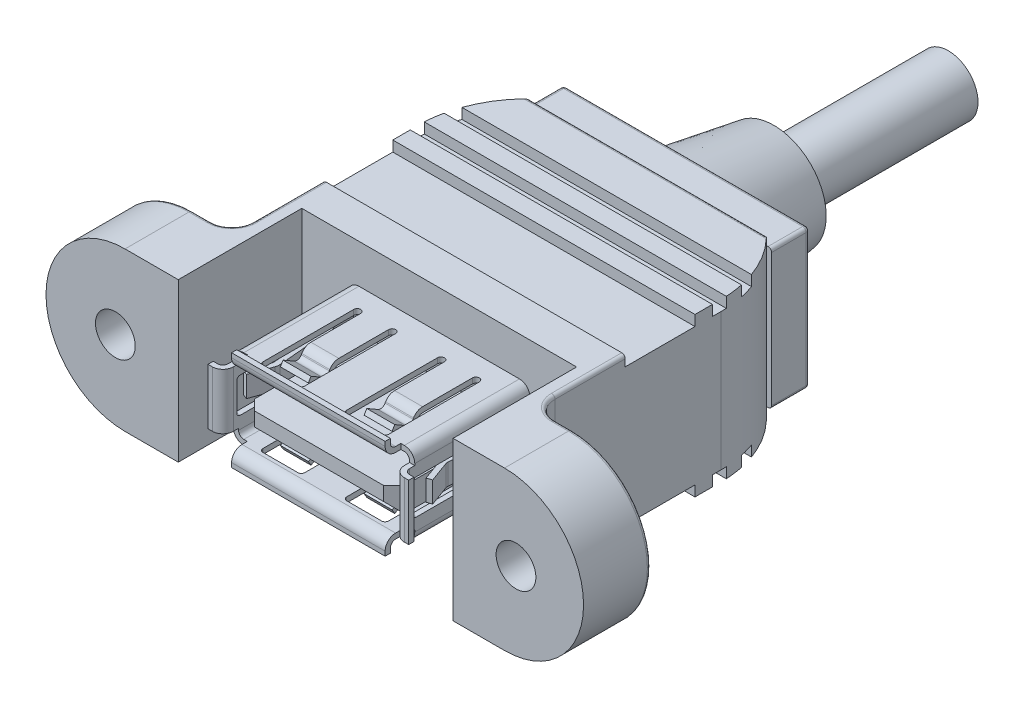
SolidWorks part; units mm, degrees
ref_plane "Front Plane" through (0, 0, 0) normal (0, 0, 1) x (1, 0, 0)
ref_plane "Top Plane" through (0, 0, 0) normal (0, 1, 0) x (1, 0, 0)
ref_plane "Right Plane" through (0, 0, 0) normal (1, 0, 0) x (0, 0, -1)
sketch "Sketch1" plane through (0, 0, 0) normal (0, 1, 0) x (1, 0, 0)
  line L0 (0, 0) -> (0, 57.7309) construction
  line L1 (-10.0012, 0) -> (-10.0013, -8.9916)
  line L2 (-10.0012, 0) -> (10.0012, 0)
  line L3 (-10.9982, -8.9916) -> (-10.9982, 9.525)
  line L4 (-8.5691, 15.24) -> (8.5691, 15.24)
  line L5 (10.9982, -8.9916) -> (10.9982, 9.525)
  line L6 (10.0012, 0) -> (10.0013, -8.9916)
  line L7 (-10.9982, -8.9916) -> (-10.0013, -8.9916)
  line L8 (10.0013, -8.9916) -> (10.9982, -8.9916)
  arc A0 (-8.5691, 15.24) -> (-10.9982, 9.525) centre (-3.0607, 9.525) ccw
  arc A1 (10.9982, 9.525) -> (8.5691, 15.24) centre (3.0607, 9.525) ccw
  dimension "D6" = 15.875
  dimension "D1" = 21.9964
  dimension "D2" = 15.24
  dimension "D3" = 20.0025
  dimension "D4" = 8.9916
  dimension "D5" = 9.525
  dimension "D7" = 10.9982
extrude "Extrude1" add sketch "Sketch1" along normal mid plane 11.5062
sketch "Sketch2" plane through (0, 0, -15.24) normal (0, 0, -1) x (-1, 0, 0)
  line L0 (0, 0) -> (-8.9535, 0) construction
  line L1 (-8.9535, 5.08) -> (8.9535, 5.08)
  line L2 (-8.9535, 5.08) -> (-8.9535, -5.08)
  line L3 (-8.9535, -5.08) -> (8.9535, -5.08)
  line L4 (8.9535, 5.08) -> (8.9535, -5.08)
  line L5 (0, 0) -> (0, -5.08) construction
  dimension "D1" = 17.907
  dimension "D2" = 10.16
extrude "Extrude2" add sketch "Sketch2" along normal blind 2.7686
sketch "Sketch3" plane through (0, 0, 8.9916) normal (0, 0, 1) x (1, 0, 0)
  line L0 (-10.9982, -5.7531) -> (-10.0013, -5.7531) construction
  line L1 (10.0012, 5.7531) -> (13.7458, 5.7531)
  line L2 (10.0012, 5.7531) -> (10.0013, -5.7531)
  line L3 (10.0013, -5.7531) -> (13.7458, -5.7531)
  line L5 (-10.0013, 5.7531) -> (-13.8758, 5.7531)
  line L6 (-10.0013, 5.7531) -> (-10.0012, -5.7531)
  line L7 (-10.0012, -5.7531) -> (-13.8758, -5.7531)
  line L9 (10.0013, -5.7531) -> (10.9982, -5.7531) construction
  arc A0 (-13.8758, 5.7531) -> (-13.8758, -5.7531) centre (-13.8758, 0) ccw
  arc A1 (13.7458, 5.7531) -> (13.7458, -5.7531) centre (13.7458, 0) cw
  dimension "D1" = 9.4976
  dimension "D2" = 9.6276
extrude "Extrude3" add sketch "Sketch3" against normal blind 4.9
sketch "Sketch4" plane through (0, 0, 0) normal (0, 1, 0) x (1, 0, 0)
  line L0 (-10.9982, -1.5516) -> (-12.7762, -4.0916)
  line L1 (10.9982, -1.5516) -> (12.7762, -4.0916)
  line L2 (-10.9982, 9.525) -> (-10.9982, -4.0916) construction
  line L3 (-10.9982, -1.5516) -> (-10.9982, -4.0916)
  line L4 (-10.9982, -4.0916) -> (-13.8758, -4.0916) construction
  line L5 (-10.9982, -4.0916) -> (-12.7762, -4.0916)
  line L6 (10.9982, -4.0916) -> (10.9982, 9.525) construction
  line L7 (10.9982, -4.0916) -> (10.9982, -1.5516)
  line L8 (13.7458, -4.0916) -> (10.9982, -4.0916) construction
  line L9 (12.7762, -4.0916) -> (10.9982, -4.0916)
  dimension "D1" = 2.54
  dimension "D2" = 1.778
extrude "Extrude4" add sketch "Sketch4" along normal mid plane 2.54
sketch "Sketch5" plane through (0, 0, 8.9916) normal (0, 0, 1) x (1, 0, 0)
  line L0 (0, 0) -> (0, 11.1761) construction
  line L1 (-7.2517, 3.4036) -> (7.2517, 3.4036) construction
  line L2 (-7.2517, 3.4036) -> (-7.2517, -3.4036) construction
  line L3 (-7.2517, -3.4036) -> (7.2517, -3.4036) construction
  line L4 (7.2517, 3.4036) -> (7.2517, -3.4036) construction
  line L5 (-14.5801, 0) -> (14.5801, 0) construction
  circle A0 centre (-14.5801, 0) radius 1.4478
  circle A1 centre (14.5801, 0) radius 1.4478
  point P8 (0, 3.4036)
  point P9 (0, 0)
  dimension "D3" = 2.8956
  dimension "D1" = 7.3284
  dimension "D5" = 14.5034
  dimension "D7" = 6.8072
  dimension "D8" = 3.4036
extrude "Cut-Extrude1" cut sketch "Sketch5" against normal up to surface (4.9 mm away) up to face at (-12.8812, 0, 4.0916)
sketch "Sketch6" plane through (0, 0, 0) normal (0, 1, 0) x (1, 0, 0)
  line L0 (0, 27.38) -> (0, 9.0652) construction
  line L1 (-8.9535, 18.0086) -> (8.9535, 18.0086) construction
  line L2 (0, 18.0086) -> (4.826, 18.0086)
  line L3 (0, 24.3586) -> (3.81, 24.3586)
  line L4 (3.81, 24.3586) -> (4.826, 18.0086)
  line L5 (0, 24.3586) -> (0, 18.0086)
  dimension "D1" = 9.652
  dimension "D2" = 7.62
  dimension "D3" = 6.35
revolve "Revolve1" add sketch "Sketch6" angle 360 about L0
sketch "Sketch9" plane through (0, 0, -24.3586) normal (0, 0, -1) x (-1, 0, 0)
  circle A0 centre (0, 0) radius 2.159
  dimension "D1" = 4.318
extrude "Extrude5" add sketch "Sketch9" along normal blind 12.7
sketch "Sketch7" plane through (0, -5.7531, 0) normal (0, -1, 0) x (1, 0, 0)
  line L0 (0, -2.54) -> (0, 0) construction
  line L1 (17.272, -2.54) -> (-17.272, -2.54)
  line L2 (17.78, -3.048) -> (17.78, -7.112)
  line L3 (17.272, -7.62) -> (-17.272, -7.62)
  line L4 (-17.78, -3.048) -> (-17.78, -7.112)
  line L5 (17.272, -8.89) -> (-17.272, -8.89)
  line L6 (-10.0012, 0) -> (10.0012, 0) construction
  line L7 (17.272, -9.906) -> (-17.272, -9.906)
  line L8 (0, -2.54) -> (0, -8.89) construction
  line L9 (16.256, -11.176) -> (-16.256, -11.176)
  line L11 (16.256, -12.192) -> (-16.256, -12.192)
  arc A0 (17.272, -8.89) -> (17.272, -9.906) centre (17.272, -9.398) cw
  arc A1 (16.256, -11.176) -> (16.256, -12.192) centre (16.256, -11.684) cw
  arc A2 (-16.256, -12.192) -> (-16.256, -11.176) centre (-16.256, -11.684) cw
  arc A3 (-17.272, -9.906) -> (-17.272, -8.89) centre (-17.272, -9.398) cw
  arc A4 (17.272, -7.62) -> (17.78, -7.112) centre (17.272, -7.112) ccw
  arc A5 (-17.78, -7.112) -> (-17.272, -7.62) centre (-17.272, -7.112) ccw
  arc A6 (-17.272, -2.54) -> (-17.78, -3.048) centre (-17.272, -3.048) ccw
  arc A7 (17.272, -2.54) -> (17.78, -3.048) centre (17.272, -3.048) cw
  dimension "D1" = 0.508
  dimension "D7" = 35.56
  dimension "D9" = 33.528
  dimension "D10" = 16.764
  dimension "D2" = 35.56
  dimension "D3" = 2.54
  dimension "D4" = 5.08
  dimension "D5" = 1.27
  dimension "D6" = 1.27
  dimension "D8" = 1.016
extrude "Cut-Extrude2" cut sketch "Sketch7" against normal blind 0.762
sketch "Sketch8" plane through (0, 5.7531, 0) normal (0, 1, 0) x (-1, 0, 0)
  line L2 (16.256, -11.176) -> (-16.256, -11.176)
  line L3 (-16.256, -12.192) -> (16.256, -12.192)
  line L4 (16.256, -11.176) -> (-16.256, -11.176)
  line L5 (-16.256, -12.192) -> (16.256, -12.192)
  line L6 (17.272, -8.89) -> (-17.272, -8.89)
  line L7 (-17.272, -9.906) -> (17.272, -9.906)
  line L8 (17.272, -8.89) -> (-17.272, -8.89)
  line L9 (-17.272, -9.906) -> (17.272, -9.906)
  line L12 (17.272, -2.54) -> (-17.272, -2.54)
  line L13 (17.78, -7.112) -> (17.78, -3.048)
  line L14 (-17.272, -7.62) -> (17.272, -7.62)
  line L15 (-17.78, -3.048) -> (-17.78, -7.112)
  line L16 (17.272, -2.54) -> (-17.272, -2.54)
  line L17 (17.78, -7.112) -> (17.78, -3.048)
  line L18 (-17.272, -7.62) -> (17.272, -7.62)
  line L19 (-17.78, -3.048) -> (-17.78, -7.112)
  arc A2 (16.256, -12.192) -> (16.256, -11.176) centre (16.256, -11.684) ccw
  arc A3 (-16.256, -11.176) -> (-16.256, -12.192) centre (-16.256, -11.684) ccw
  arc A4 (16.256, -12.192) -> (16.256, -11.176) centre (16.256, -11.684) ccw
  arc A5 (-16.256, -11.176) -> (-16.256, -12.192) centre (-16.256, -11.684) ccw
  arc A6 (17.272, -9.906) -> (17.272, -8.89) centre (17.272, -9.398) ccw
  arc A7 (-17.272, -8.89) -> (-17.272, -9.906) centre (-17.272, -9.398) ccw
  arc A8 (17.272, -9.906) -> (17.272, -8.89) centre (17.272, -9.398) ccw
  arc A9 (-17.272, -8.89) -> (-17.272, -9.906) centre (-17.272, -9.398) ccw
  arc A12 (17.78, -3.048) -> (17.272, -2.54) centre (17.272, -3.048) ccw
  arc A13 (17.272, -7.62) -> (17.78, -7.112) centre (17.272, -7.112) ccw
  arc A14 (-17.78, -7.112) -> (-17.272, -7.62) centre (-17.272, -7.112) ccw
  arc A15 (-17.272, -2.54) -> (-17.78, -3.048) centre (-17.272, -3.048) ccw
  arc A16 (17.78, -3.048) -> (17.272, -2.54) centre (17.272, -3.048) ccw
  arc A17 (17.272, -7.62) -> (17.78, -7.112) centre (17.272, -7.112) ccw
  arc A18 (-17.78, -7.112) -> (-17.272, -7.62) centre (-17.272, -7.112) ccw
  arc A19 (-17.272, -2.54) -> (-17.78, -3.048) centre (-17.272, -3.048) ccw
  dimension "D1" = 0
  dimension "D2" = 0
  dimension "D3" = 0
extrude "Cut-Extrude3" cut sketch "Sketch8" against normal blind 0.762
fillet "Fillet1" radius 1.524 4 edges at (-10.9982, -3.5116, 4.0916) (-10.9982, 3.5116, 4.0916) (10.9982, -3.5116, 4.0916) (10.9982, 3.5116, 4.0916)
fillet "Fillet2" radius 0.254 24 edges at (0, -5.7531, -15.24) (-10.9982, -5.7531, 0.0138) (-10.9982, 5.7531, 0.0138) (-13.199, 5.7531, 4.0916) (10.9982, 5.7531, 0.0138) (10.9982, -5.7531, 0.0138) (13.134, -5.7531, 4.0916) (-11.4446, -5.7531, 3.6452) (-11.4446, 5.7531, 3.6452) (11.4446, -5.7531, 3.6452) (11.4446, 5.7531, 3.6452) (8.9535, 5.08, -16.6243) (8.9535, -5.08, -16.6243) (-8.9535, -5.08, -16.6243) (-8.9535, 5.08, -16.6243) (8.9535, 0, -18.0086) (0, -5.08, -18.0086) (-8.9535, 0, -18.0086) (0, 5.08, -18.0086) (13.134, 5.7531, 4.0916) (19.4989, 0, 4.0916) (-13.199, -5.7531, 4.0916) (-19.6289, 0, 4.0916) (0, 5.7531, -15.24)
sketch "Sketch10" plane through (0, 0, 0) normal (0, 0, 1) x (1, 0, 0)
  line L0 (-22.3107, 0) -> (0, 0) construction
  line L1 (0, 8.8149) -> (0, -8.8149) construction
  line L2 (-5.842, 2.54) -> (5.842, 2.54)
  line L3 (-5.842, 2.921) -> (5.842, 2.921)
  line L4 (-6.604, 2.159) -> (-6.604, -2.159)
  line L5 (-5.842, -2.921) -> (5.842, -2.921)
  line L6 (6.604, 2.159) -> (6.604, -2.159)
  line L7 (6.223, 2.159) -> (6.223, -2.159)
  line L8 (-5.842, -2.54) -> (5.842, -2.54)
  line L9 (-6.223, 2.159) -> (-6.223, -2.159)
  arc A0 (-6.604, 2.159) -> (-5.842, 2.921) centre (-5.842, 2.159) cw
  arc A1 (-5.842, -2.921) -> (-6.604, -2.159) centre (-5.842, -2.159) cw
  arc A2 (6.604, -2.159) -> (5.842, -2.921) centre (5.842, -2.159) cw
  arc A3 (5.842, 2.921) -> (6.604, 2.159) centre (5.842, 2.159) cw
  arc A4 (-6.223, 2.159) -> (-5.842, 2.54) centre (-5.842, 2.159) cw
  arc A5 (5.842, 2.54) -> (6.223, 2.159) centre (5.842, 2.159) cw
  arc A6 (6.223, -2.159) -> (5.842, -2.54) centre (5.842, -2.159) cw
  arc A7 (-5.842, -2.54) -> (-6.223, -2.159) centre (-5.842, -2.159) cw
  point P13 (-6.604, -2.921)
  point P16 (6.604, -2.921)
  dimension "D6" = 0.762
  dimension "D2" = 13.208
  dimension "D3" = 6.604
  dimension "D4" = 5.842
  dimension "D5" = 2.921
  dimension "D7" = 0.381
extrude "Extrude6" add sketch "Sketch10" along normal blind 8.382
sketch "Sketch11" plane through (0, 0, 8.382) normal (0, 0, 1) x (1, 0, 0)
  line L0 (-6.604, 2.159) -> (-6.604, -2.159) construction
  line L1 (-6.604, 2.032) -> (-6.223, 2.032)
  line L2 (-6.604, 2.032) -> (-6.604, -2.032)
  line L3 (-6.604, -2.032) -> (-6.223, -2.032)
  line L4 (-6.223, 2.032) -> (-6.223, -2.032)
  line L5 (-6.223, 2.159) -> (-6.223, -2.159) construction
  line L6 (-5.842, -2.54) -> (5.842, -2.54) construction
  line L7 (-5.588, -2.54) -> (5.588, -2.54)
  line L8 (-5.588, -2.54) -> (-5.588, -2.921)
  line L9 (-5.588, -2.921) -> (5.588, -2.921)
  line L10 (5.588, -2.54) -> (5.588, -2.921)
  line L11 (-5.842, -2.921) -> (5.842, -2.921) construction
  line L12 (5.842, 2.921) -> (-5.842, 2.921) construction
  line L13 (-5.588, 2.921) -> (5.588, 2.921)
  line L14 (-5.588, 2.921) -> (-5.588, 2.54)
  line L15 (-5.588, 2.54) -> (5.588, 2.54)
  line L16 (5.588, 2.921) -> (5.588, 2.54)
  line L17 (5.842, 2.54) -> (-5.842, 2.54) construction
  line L18 (6.223, -2.159) -> (6.223, 2.159) construction
  line L19 (6.223, 2.032) -> (6.604, 2.032)
  line L20 (6.223, 2.032) -> (6.223, -2.032)
  line L21 (6.223, -2.032) -> (6.604, -2.032)
  line L22 (6.604, 2.032) -> (6.604, -2.032)
  line L23 (6.604, -2.159) -> (6.604, 2.159) construction
  dimension "D1" = 11.176
  dimension "D2" = 4.064
  dimension "D3" = 0.889
  dimension "D4" = 1.016
extrude "Extrude7" add sketch "Sketch11" along normal blind 0.254
sketch "Sketch12" plane through (5.588, 0, 0) normal (1, 0, 0) x (0, 0, -1)
  line L0 (-9.525, 3.302) -> (-9.525, 3.6195)
  line L1 (-9.144, 3.302) -> (-9.144, 3.6195)
  line L2 (-9.525, 3.6195) -> (-9.144, 3.6195)
  line L3 (-9.525, -3.302) -> (-9.525, -3.6195)
  line L4 (-8.382, 2.54) -> (-8.382, 2.921)
  line L5 (-8.382, 2.921) -> (-8.636, 2.921)
  line L6 (-8.636, 2.921) -> (-8.636, 2.54)
  line L7 (-8.636, 2.54) -> (-8.382, 2.54)
  line L8 (-8.382, 2.54) -> (-8.382, 2.921)
  line L9 (-8.382, 2.921) -> (-8.763, 2.921)
  line L10 (-8.382, -2.921) -> (-8.382, -2.54)
  line L11 (-8.763, 2.54) -> (-8.382, 2.54)
  line L12 (-8.382, -2.54) -> (-8.636, -2.54)
  line L13 (-8.636, -2.54) -> (-8.636, -2.921)
  line L14 (-8.636, -2.921) -> (-8.382, -2.921)
  line L15 (-8.382, -2.921) -> (-8.382, -2.54)
  line L16 (-8.382, -2.54) -> (-8.763, -2.54)
  line L17 (-9.144, -3.302) -> (-9.144, -3.6195)
  line L18 (-8.763, -2.921) -> (-8.382, -2.921)
  line L19 (-9.525, -3.6195) -> (-9.144, -3.6195)
  line L20 (0, 0) -> (-11.5715, 0) construction
  line L25 (0, 5.7531) -> (0, -5.7531) construction
  arc A0 (-8.763, 2.54) -> (-9.525, 3.302) centre (-8.763, 3.302) cw
  arc A1 (-8.763, -2.54) -> (-9.525, -3.302) centre (-8.763, -3.302) ccw
  arc A2 (-8.763, 2.921) -> (-9.144, 3.302) centre (-8.763, 3.302) cw
  arc A3 (-8.763, -2.921) -> (-9.144, -3.302) centre (-8.763, -3.302) ccw
  dimension "D7" = 0.762
  dimension "D8" = 0.381
  dimension "D3" = 1.0795
  dimension "D4" = 1.0795
  dimension "D5" = 0.381
  dimension "D6" = 9.525
  dimension "D1" = 0
  dimension "D2" = 0
extrude "Extrude8" add sketch "Sketch12" against normal blind 11.176
sketch "Sketch13" plane through (0, 2.032, 0) normal (0, 1, 0) x (-1, 0, 0)
  line L0 (-6.985, 9.144) -> (-7.3025, 9.144)
  line L1 (-7.3025, 9.144) -> (-7.3025, 9.525)
  line L2 (-7.3025, 9.525) -> (-6.985, 9.525)
  line L3 (6.985, 9.144) -> (7.3025, 9.144)
  line L4 (6.223, 8.382) -> (6.604, 8.382)
  line L5 (6.604, 8.382) -> (6.604, 8.636)
  line L6 (6.604, 8.636) -> (6.223, 8.636)
  line L7 (6.223, 8.636) -> (6.223, 8.382)
  line L8 (6.223, 8.382) -> (6.604, 8.382)
  line L9 (6.604, 8.382) -> (6.604, 8.763)
  line L10 (7.3025, 9.144) -> (7.3025, 9.525)
  line L11 (6.223, 8.763) -> (6.223, 8.382)
  line L12 (-6.604, 8.382) -> (-6.223, 8.382)
  line L13 (-6.223, 8.382) -> (-6.223, 8.636)
  line L14 (-6.223, 8.636) -> (-6.604, 8.636)
  line L15 (-6.604, 8.636) -> (-6.604, 8.382)
  line L16 (-6.604, 8.382) -> (-6.223, 8.382)
  line L17 (-6.223, 8.382) -> (-6.223, 8.763)
  line L18 (7.3025, 9.525) -> (6.985, 9.525)
  line L19 (-6.604, 8.763) -> (-6.604, 8.382)
  line L20 (5.588, 9.525) -> (-5.588, 9.525) construction
  arc A0 (-6.985, 9.144) -> (-6.604, 8.763) centre (-6.985, 8.763) cw
  arc A1 (6.985, 9.144) -> (6.604, 8.763) centre (6.985, 8.763) ccw
  arc A2 (-6.223, 8.763) -> (-6.985, 9.525) centre (-6.985, 8.763) ccw
  arc A3 (6.985, 9.525) -> (6.223, 8.763) centre (6.985, 8.763) ccw
  point P26 (6.223, 9.525)
  dimension "D6" = 0.381
  dimension "D7" = 0.762
  dimension "D3" = 0.381
  dimension "D4" = 1.0795
  dimension "D5" = 1.0795
  dimension "D1" = 0
  dimension "D2" = 0
extrude "Extrude9" add sketch "Sketch13" against normal up to surface (4.064 mm away) up to face at (-6.4611, -2.032, 8.5725)
sketch "Sketch14" plane through (0, 2.921, 0) normal (0, 1, 0) x (-1, 0, 0)
  line L0 (0, 0) -> (0, 2.9776) construction
  line L1 (-2.032, 1.651) -> (-2.032, 2.159)
  line L2 (4.572, 1.651) -> (4.572, 8.255)
  line L3 (4.318, 8.509) -> (1.778, 8.509)
  line L4 (1.524, 1.651) -> (1.524, 8.255)
  line L5 (-3.048, 8.509) -> (-3.048, 0.7388) construction
  line L6 (-1.524, 1.651) -> (-1.524, 8.255)
  line L7 (-1.778, 8.509) -> (-4.318, 8.509)
  line L8 (-4.572, 1.651) -> (-4.572, 8.255)
  line L9 (-5.842, 0) -> (5.842, 0) construction
  line L10 (3.048, 8.509) -> (3.048, 0.7388) construction
  line L11 (-2.032, 2.159) -> (-4.064, 2.159)
  line L12 (5.588, 9.525) -> (-5.588, 9.525) construction
  line L13 (-4.064, 2.159) -> (-4.064, 1.651)
  line L14 (4.064, 1.651) -> (4.064, 2.159)
  line L15 (4.064, 2.159) -> (2.032, 2.159)
  line L16 (2.032, 2.159) -> (2.032, 1.651)
  arc A0 (-4.572, 8.255) -> (-4.318, 8.509) centre (-4.318, 8.255) cw
  arc A1 (-1.524, 8.255) -> (-1.778, 8.509) centre (-1.778, 8.255) ccw
  arc A2 (-2.032, 1.651) -> (-1.524, 1.651) centre (-1.778, 1.651) ccw
  arc A3 (-4.572, 1.651) -> (-4.064, 1.651) centre (-4.318, 1.651) ccw
  arc A4 (2.032, 1.651) -> (1.524, 1.651) centre (1.778, 1.651) cw
  arc A5 (4.572, 1.651) -> (4.064, 1.651) centre (4.318, 1.651) cw
  arc A6 (4.318, 8.509) -> (4.572, 8.255) centre (4.318, 8.255) cw
  arc A7 (1.524, 8.255) -> (1.778, 8.509) centre (1.778, 8.255) cw
  dimension "D6" = 7.112
  dimension "D1" = 0.254
  dimension "D7" = 0.762
  dimension "D2" = 1.016
  dimension "D3" = 3.048
  dimension "D4" = 6.096
  dimension "D5" = 3.048
extrude "Cut-Extrude4" cut sketch "Sketch14" against normal up to surface (5.842 mm away) up to face at (0, -2.921, 6.3818)
sketch "Sketch15" plane through (6.604, 0, 0) normal (1, 0, 0) x (0, 0, -1)
  line L0 (0, 0) -> (-4.7284, 0) construction
  line L1 (0, -2.159) -> (0, 2.159) construction
  line L2 (-9.525, -2.032) -> (-9.525, 2.032) construction
  line L3 (-8.255, 1.27) -> (-1.651, 1.27)
  line L4 (-8.509, 1.016) -> (-8.509, -1.016)
  line L5 (-8.255, -1.27) -> (-1.651, -1.27)
  line L6 (-1.651, 0.762) -> (-1.905, 0.762)
  line L7 (-1.905, 0.762) -> (-1.905, -0.762)
  line L8 (-1.905, -0.762) -> (-1.651, -0.762)
  arc A0 (-8.509, 1.016) -> (-8.255, 1.27) centre (-8.255, 1.016) cw
  arc A1 (-8.255, -1.27) -> (-8.509, -1.016) centre (-8.255, -1.016) cw
  arc A2 (-1.651, -0.762) -> (-1.651, -1.27) centre (-1.651, -1.016) cw
  arc A3 (-1.651, 1.27) -> (-1.651, 0.762) centre (-1.651, 1.016) cw
  point P12 (-8.509, 1.27)
  point P15 (-8.509, -1.27)
  dimension "D5" = 0.254
  dimension "D2" = 7.112
  dimension "D6" = 0.508
  dimension "D1" = 1.016
  dimension "D3" = 1.27
  dimension "D4" = 2.54
extrude "Cut-Extrude5" cut sketch "Sketch15" against normal blind 13.462
sketch "Sketch17" plane through (4.064, 0, 0) normal (1, 0, 0) x (0, 0, -1)
  line L0 (-5.935, 2.54) -> (-5.9716, 2.4765)
  line L1 (-8.509, 2.54) -> (-8.509, 2.921) construction
  line L2 (-6.4921, 2.337) -> (-7.3025, 2.8049)
  line L3 (-5.605, 2.3495) -> (-5.6417, 2.286)
  line L4 (-2.159, 2.54) -> (-1.651, 2.54)
  line L5 (-1.651, 2.54) -> (-1.651, 2.921)
  line L6 (-1.651, 2.921) -> (-2.159, 2.921)
  line L7 (-2.159, 2.921) -> (-2.159, 2.54)
  line L8 (-5.2751, 2.54) -> (-1.651, 2.54)
  line L9 (-1.651, 2.54) -> (-1.651, 2.921)
  line L10 (-1.651, 2.921) -> (-5.2751, 2.921)
  line L11 (-5.2751, 2.921) -> (-5.715, 2.921) construction
  line L12 (-6.6826, 2.0071) -> (-7.493, 2.475)
  line L13 (-7.493, 2.475) -> (-7.3025, 2.8049)
  line L14 (-5.715, 2.921) -> (-5.935, 2.54) construction
  line L15 (-5.6417, -2.286) -> (-5.605, -2.3495)
  line L16 (-6.6826, -2.0071) -> (-7.493, -2.475)
  line L17 (-5.935, -2.54) -> (-5.9716, -2.4765)
  line L18 (-6.4921, -2.337) -> (-7.3025, -2.8049)
  line L19 (-1.651, -2.54) -> (-2.159, -2.54)
  line L20 (-2.159, -2.54) -> (-2.159, -2.921)
  line L21 (-2.159, -2.921) -> (-1.651, -2.921)
  line L22 (-1.651, -2.921) -> (-1.651, -2.54)
  line L23 (-1.651, -2.54) -> (-5.2751, -2.54)
  line L24 (-7.493, -2.475) -> (-7.3025, -2.8049)
  line L25 (-5.2751, -2.921) -> (-1.651, -2.921)
  line L26 (-1.651, -2.921) -> (-1.651, -2.54)
  arc A0 (-6.4921, 2.337) -> (-5.9716, 2.4765) centre (-6.3016, 2.667) ccw
  arc A1 (-6.6826, 2.0071) -> (-5.6417, 2.286) centre (-6.3016, 2.667) ccw
  arc A2 (-5.2751, 2.921) -> (-5.935, 2.54) centre (-5.2751, 2.159) ccw
  arc A3 (-5.2751, 2.54) -> (-5.605, 2.3495) centre (-5.2751, 2.159) ccw
  arc A4 (-5.2751, -2.54) -> (-5.605, -2.3495) centre (-5.2751, -2.159) cw
  arc A5 (-5.9716, -2.4765) -> (-6.4921, -2.337) centre (-6.3016, -2.667) ccw
  arc A6 (-5.2751, -2.921) -> (-5.935, -2.54) centre (-5.2751, -2.159) cw
  arc A7 (-6.6826, -2.0071) -> (-5.6417, -2.286) centre (-6.3016, -2.667) cw
  dimension "D3" = 0.762
  dimension "D7" = 0.762
  dimension "D8" = 0.381
  dimension "D9" = 4.064
  dimension "D12" = 0.381
  dimension "D13" = 0.762
  dimension "D16" = 1.016
  dimension "D2" = 0.381
  dimension "D4" = 60
  dimension "D5" = 1.016
  dimension "D6" = 1.016
  dimension "D10" = 90
  dimension "D14" = 0.381
  dimension "D15" = 0.381
  dimension "D17" = 60
  dimension "D18" = 90
  dimension "D1" = 0
  dimension "D11" = 0
extrude "Extrude10" add sketch "Sketch17" against normal blind 2.032
sketch "Sketch18" plane through (-2.032, 0, 0) normal (1, 0, 0) x (0, 0, -1)
  line L8 (-5.935, 2.54) -> (-5.9716, 2.4765)
  line L9 (-6.4921, 2.337) -> (-7.3025, 2.8049)
  line L10 (-7.3025, 2.8049) -> (-7.493, 2.475)
  line L11 (-7.493, 2.475) -> (-6.6826, 2.0071)
  line L12 (-5.6417, 2.286) -> (-5.605, 2.3495)
  line L13 (-5.2751, 2.54) -> (-1.651, 2.54)
  line L14 (-1.651, 2.54) -> (-1.651, 2.921)
  line L15 (-1.651, 2.921) -> (-5.2751, 2.921)
  line L16 (-5.935, 2.54) -> (-5.9716, 2.4765)
  line L17 (-6.4921, 2.337) -> (-7.3025, 2.8049)
  line L18 (-7.3025, 2.8049) -> (-7.493, 2.475)
  line L19 (-7.493, 2.475) -> (-6.6826, 2.0071)
  line L20 (-5.6417, 2.286) -> (-5.605, 2.3495)
  line L21 (-5.2751, 2.54) -> (-1.651, 2.54)
  line L22 (-1.651, 2.54) -> (-1.651, 2.921)
  line L23 (-1.651, 2.921) -> (-5.2751, 2.921)
  line L24 (-5.605, -2.3495) -> (-5.6417, -2.286)
  line L25 (-1.651, -2.54) -> (-5.2751, -2.54)
  line L26 (-1.651, -2.921) -> (-1.651, -2.54)
  line L27 (-5.2751, -2.921) -> (-1.651, -2.921)
  line L28 (-5.9716, -2.4765) -> (-5.935, -2.54)
  line L29 (-7.3025, -2.8049) -> (-6.4921, -2.337)
  line L30 (-7.493, -2.475) -> (-7.3025, -2.8049)
  line L31 (-6.6826, -2.0071) -> (-7.493, -2.475)
  line L32 (-5.605, -2.3495) -> (-5.6417, -2.286)
  line L33 (-1.651, -2.54) -> (-5.2751, -2.54)
  line L34 (-1.651, -2.921) -> (-1.651, -2.54)
  line L35 (-5.2751, -2.921) -> (-1.651, -2.921)
  line L36 (-5.9716, -2.4765) -> (-5.935, -2.54)
  line L37 (-7.3025, -2.8049) -> (-6.4921, -2.337)
  line L38 (-7.493, -2.475) -> (-7.3025, -2.8049)
  line L39 (-6.6826, -2.0071) -> (-7.493, -2.475)
  arc A4 (-6.4921, 2.337) -> (-5.9716, 2.4765) centre (-6.3016, 2.667) ccw
  arc A5 (-6.6826, 2.0071) -> (-5.6417, 2.286) centre (-6.3016, 2.667) ccw
  arc A6 (-5.2751, 2.54) -> (-5.605, 2.3495) centre (-5.2751, 2.159) ccw
  arc A7 (-5.2751, 2.921) -> (-5.935, 2.54) centre (-5.2751, 2.159) ccw
  arc A8 (-6.4921, 2.337) -> (-5.9716, 2.4765) centre (-6.3016, 2.667) ccw
  arc A9 (-6.6826, 2.0071) -> (-5.6417, 2.286) centre (-6.3016, 2.667) ccw
  arc A10 (-5.2751, 2.54) -> (-5.605, 2.3495) centre (-5.2751, 2.159) ccw
  arc A11 (-5.2751, 2.921) -> (-5.935, 2.54) centre (-5.2751, 2.159) ccw
  arc A12 (-5.605, -2.3495) -> (-5.2751, -2.54) centre (-5.2751, -2.159) ccw
  arc A13 (-5.935, -2.54) -> (-5.2751, -2.921) centre (-5.2751, -2.159) ccw
  arc A14 (-5.9716, -2.4765) -> (-6.4921, -2.337) centre (-6.3016, -2.667) ccw
  arc A15 (-5.6417, -2.286) -> (-6.6826, -2.0071) centre (-6.3016, -2.667) ccw
  arc A16 (-5.605, -2.3495) -> (-5.2751, -2.54) centre (-5.2751, -2.159) ccw
  arc A17 (-5.935, -2.54) -> (-5.2751, -2.921) centre (-5.2751, -2.159) ccw
  arc A18 (-5.9716, -2.4765) -> (-6.4921, -2.337) centre (-6.3016, -2.667) ccw
  arc A19 (-5.6417, -2.286) -> (-6.6826, -2.0071) centre (-6.3016, -2.667) ccw
  dimension "D1" = 0
  dimension "D2" = 0
extrude "Extrude11" add sketch "Sketch18" against normal blind 2.032
sketch "Sketch20" plane through (0, 0.762, 0) normal (0, 1, 0) x (-1, 0, 0)
  line L0 (-6.6011, 2.4461) -> (-6.318, 5.6818)
  line L1 (-6.3395, 5.8453) -> (-6.8918, 7.3627)
  line L2 (-6.223, 2.3964) -> (-5.9385, 5.6486)
  line L3 (-5.9815, 5.9756) -> (-6.5338, 7.493)
  line L4 (-6.223, 1.651) -> (-6.223, 1.905)
  line L5 (-6.223, 1.905) -> (-6.604, 1.905)
  line L6 (-6.604, 1.905) -> (-6.604, 1.651)
  line L7 (-6.604, 1.651) -> (-6.223, 1.651)
  line L8 (-6.223, 1.651) -> (-6.223, 2.3964)
  line L9 (-6.5338, 7.493) -> (-6.8918, 7.3627)
  line L10 (-6.604, 2.3797) -> (-6.604, 1.651)
  line L11 (-6.604, 1.651) -> (-6.223, 1.651)
  line L12 (-6.223, 8.509) -> (-6.604, 8.509) construction
  line L13 (6.6011, 2.4461) -> (6.318, 5.6818)
  line L14 (6.3395, 5.8453) -> (6.8918, 7.3627)
  line L15 (6.223, 2.3964) -> (5.9385, 5.6486)
  line L16 (5.9815, 5.9756) -> (6.5338, 7.493)
  line L17 (6.223, 1.905) -> (6.223, 1.651)
  line L18 (6.223, 1.651) -> (6.604, 1.651)
  line L19 (6.604, 1.651) -> (6.604, 1.905)
  line L20 (6.604, 1.905) -> (6.223, 1.905)
  line L21 (6.223, 2.3964) -> (6.223, 1.651)
  line L22 (6.223, 1.651) -> (6.604, 1.651)
  line L23 (6.604, 1.651) -> (6.604, 2.3797)
  line L24 (6.8918, 7.3627) -> (6.5338, 7.493)
  line L25 (6.604, 8.509) -> (6.223, 8.509) construction
  arc A0 (-6.3395, 5.8453) -> (-6.318, 5.6818) centre (-6.6976, 5.715) cw
  arc A1 (-5.9815, 5.9756) -> (-5.9385, 5.6486) centre (-6.6976, 5.715) cw
  arc A2 (5.9815, 5.9756) -> (5.9385, 5.6486) centre (6.6976, 5.715) ccw
  arc A3 (6.3395, 5.8453) -> (6.318, 5.6818) centre (6.6976, 5.715) ccw
  arc A4 (-6.6011, 2.4461) -> (-6.604, 2.3797) centre (-5.842, 2.3797) ccw
  arc A5 (6.6011, 2.4461) -> (6.604, 2.3797) centre (5.842, 2.3797) cw
  point P34 (-6.604, 2.413)
  point P37 (6.604, 2.413)
  dimension "D6" = 0.381
  dimension "D7" = 0.762
  dimension "D15" = 0.762
  dimension "D16" = 0.381
  dimension "D19" = 4.064
  dimension "D21" = 0.762
  dimension "D2" = 0.762
  dimension "D3" = 5
  dimension "D4" = 0.381
  dimension "D5" = 0.381
  dimension "D8" = 1.016
  dimension "D9" = 25
  dimension "D10" = 4.064
  dimension "D12" = 0.762
  dimension "D13" = 5
  dimension "D14" = 0.381
  dimension "D17" = 1.016
  dimension "D18" = 25
  dimension "D20" = 0.381
  dimension "D1" = 0
  dimension "D11" = 0
extrude "Extrude12" add sketch "Sketch20" against normal blind 1.524
sketch "Sketch21" plane through (0, 0, 0) normal (0, 0, 1) x (1, 0, 0)
  line L0 (-6.223, 2.159) -> (-6.223, -2.159) construction
  line L1 (-5.461, -1.778) -> (5.461, -1.778)
  line L2 (-5.461, -1.778) -> (-5.461, 0)
  line L3 (-5.461, 0) -> (5.461, 0)
  line L4 (5.461, -1.778) -> (5.461, 0)
  line L5 (6.223, -2.159) -> (6.223, 2.159) construction
  line L7 (-5.842, -2.54) -> (5.842, -2.54) construction
  dimension "D1" = 0.762
  dimension "D2" = 0.762
  dimension "D3" = 0.762
  dimension "D4" = 1.778
extrude "Extrude14" add sketch "Sketch21" along normal blind 8.7376
chamfer "Chamfer2" distance 0.762 angle 45 2 edges at (-5.461, -0.889, 8.7376) (0, -1.778, 8.7376)
